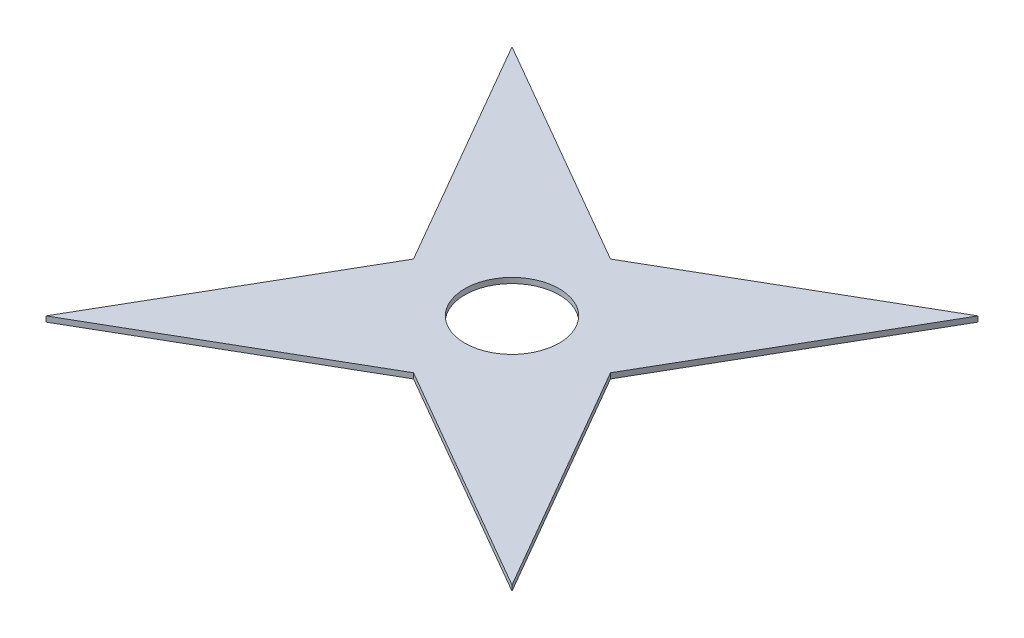
SolidWorks part; units mm, degrees
ref_plane "Front Plane" through (0, 0, 0) normal (0, 0, 1) x (1, 0, 0)
ref_plane "Top Plane" through (0, 0, 0) normal (0, 1, 0) x (1, 0, 0)
ref_plane "Right Plane" through (0, 0, 0) normal (1, 0, 0) x (0, 0, -1)
sketch "Sketch1" plane through (0, 0, 0) normal (0, 1, 0) x (1, 0, 0)
  line L0 (0, 0) -> (0, 234.4789) construction
  line L1 (0, 0) -> (250.2537, 0) construction
  line L2 (0, 0) -> (37.5, 64.9519)
  line L3 (0, 0) -> (64.9519, 37.5)
  line L5 (64.9519, 64.9519) -> (64.9519, 0) construction
  line L6 (129.9038, 0) -> (64.9519, 37.5)
  line L7 (129.9038, 0) -> (92.4038, 64.9519)
  line L8 (37.5, 64.9519) -> (92.4038, 64.9519) construction
  line L9 (129.9038, 129.9038) -> (92.4038, 64.9519)
  line L10 (129.9038, 129.9038) -> (64.9519, 92.4038)
  line L11 (0, 129.9038) -> (64.9519, 92.4038)
  line L12 (0, 129.9038) -> (37.5, 64.9519)
  circle A0 centre (64.9519, 64.9519) radius 13.155
  dimension "D5" = 26.31
  dimension "D1" = 75
  dimension "D2" = 30
  dimension "D3" = 30
  dimension "D4" = 75
extrude "Boss-Extrude1" add sketch "Sketch1" along normal blind 1.5
